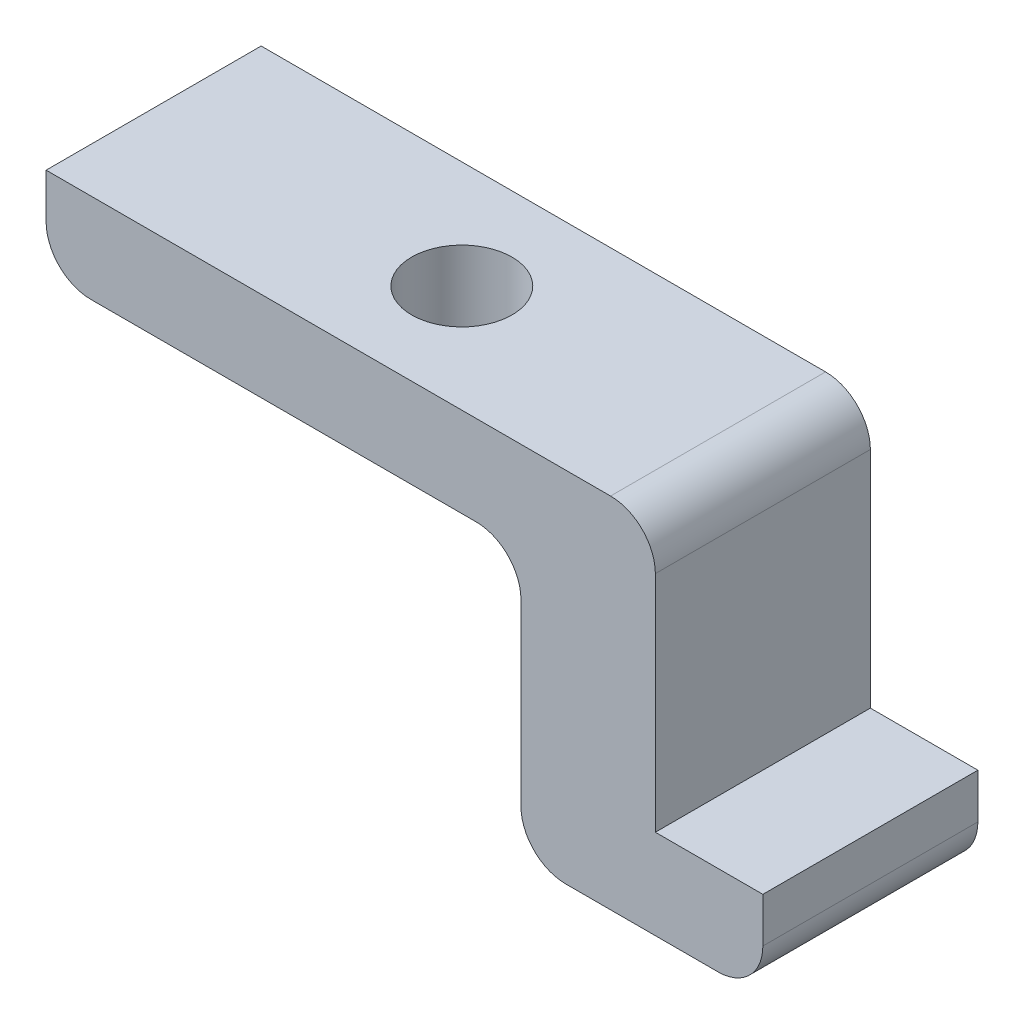
SolidWorks part; units mm, degrees
material "6061-T6 (SS)"
ref_plane "Front Plane" through (0, 0, 0) normal (0, 0, 1) x (1, 0, 0)
ref_plane "Top Plane" through (0, 0, 0) normal (0, 1, 0) x (1, 0, 0)
ref_plane "Right Plane" through (0, 0, 0) normal (1, 0, 0) x (0, 0, -1)
sketch "Sketch1" plane through (0, 0, 0) normal (0, 0, 1) x (1, 0, 0)
  line L0 (0, 0) -> (0, 9.525)
  line L1 (0, 0) -> (3.81, 0)
  line L2 (0, 9.525) -> (-21.59, 9.525)
  line L3 (-21.59, 9.525) -> (-21.59, 6.35)
  line L4 (-21.59, 6.35) -> (-4.7625, 6.35)
  line L5 (-4.7625, 6.35) -> (-4.7625, -3.175)
  line L6 (-4.7625, -3.175) -> (3.81, -3.175)
  line L7 (3.81, -3.175) -> (3.81, 0)
  line L8 (-21.59, 9.525) -> (-10.2744, 9.525)
  dimension "D1" = 9.525
  dimension "D2" = 21.59
  dimension "D3" = 3.81
  dimension "D4" = 4.7625
  dimension "D5" = 3.175
  dimension "D6" = 3.175
extrude "Boss-Extrude1" add sketch "Sketch1" along normal blind 7.62 contours L7 L1 L0 L2 L3 L4 L5 L6
sketch "Sketch2" plane through (0, 9.525, 0) normal (0, 1, 0) x (1, 0, 0)
  line L0 (-21.59, -7.62) -> (-21.59, 0) construction
  circle A0 centre (-10.668, -3.81) radius 1.778
  dimension "D2" = 3.556
  dimension "D1" = 10.922
extrude "Cut-Extrude1" cut sketch "Sketch2" against normal through all
fillet "Fillet1" radius 1.5875 5 edges at (-21.59, 6.35, 3.81) (3.81, -3.175, 3.81) (0, 9.525, 3.81) (-4.7625, 6.35, 3.81) (-4.7625, -3.175, 3.81)
